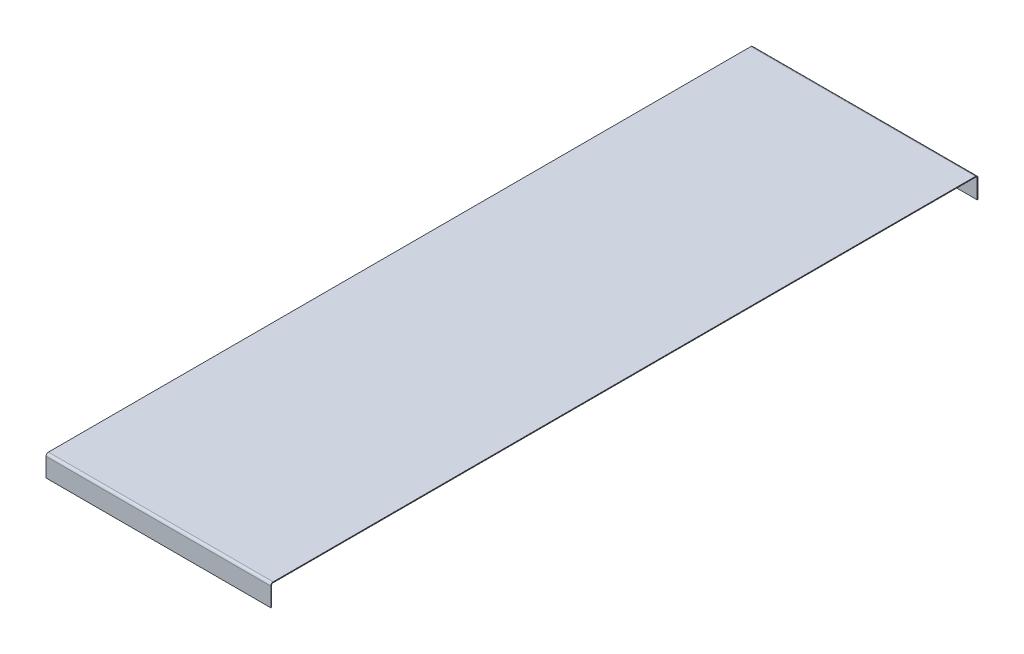
SolidWorks part; units mm, degrees
ref_plane "Front Plane" through (0, 0, 0) normal (0, 0, 1) x (1, 0, 0)
ref_plane "Top Plane" through (0, 0, 0) normal (0, 1, 0) x (1, 0, 0)
ref_plane "Right Plane" through (0, 0, 0) normal (1, 0, 0) x (0, 0, -1)
sketch "Sketch1" plane through (0, 0, 0) normal (0, 1, 0) x (1, 0, 0)
  line L1 (244.3191, -147.4761) -> (104.6191, -147.4761)
  line L2 (244.3191, -147.4761) -> (244.3191, 292.1339)
  line L3 (244.3191, 292.1339) -> (104.6191, 292.1339)
  line L4 (104.6191, -147.4761) -> (104.6191, 292.1339)
  dimension "D1" = 439.61
  dimension "D2" = 139.7
extrude "Boss-Extrude1" add sketch "Sketch1" along normal blind 0.5
sketch "Sketch2" plane through (0, 0, 0) normal (0, -1, 0) x (1, 0, 0)
  line L0 (104.6191, -292.1339) -> (104.6191, 147.4761) construction
  line L1 (244.3191, 147.4761) -> (104.6191, 147.4761)
  line L2 (244.3191, 147.4761) -> (244.3191, 146.9761)
  line L3 (244.3191, 146.9761) -> (104.6191, 146.9761)
  line L4 (104.6191, 147.4761) -> (104.6191, 146.9761)
  dimension "D1" = 0.5
extrude "Boss-Extrude2" add sketch "Sketch2" along normal blind 12.7
fillet "Fillet1" radius 1 1 edges at (174.4691, 0, 146.9761)
fillet "Fillet2" radius 1.5 1 edges at (174.4691, 0.5, 147.4761)
sketch "Sketch4" plane through (0, 0, 0) normal (0, -1, 0) x (1, 0, 0)
  line L0 (104.6191, -292.1339) -> (104.6191, 145.9761) construction
  line L1 (244.3191, -292.1339) -> (104.6191, -292.1339)
  line L2 (244.3191, -292.1339) -> (244.3191, -291.6339)
  line L3 (244.3191, -291.6339) -> (104.6191, -291.6339)
  line L4 (104.6191, -292.1339) -> (104.6191, -291.6339)
  dimension "D1" = 0.5
extrude "Boss-Extrude3" add sketch "Sketch4" along normal blind 12.7
fillet "Fillet3" radius 1 1 edges at (174.4691, 0, -291.6339)
fillet "Fillet4" radius 1.5 1 edges at (174.4691, 0.5, -292.1339)
